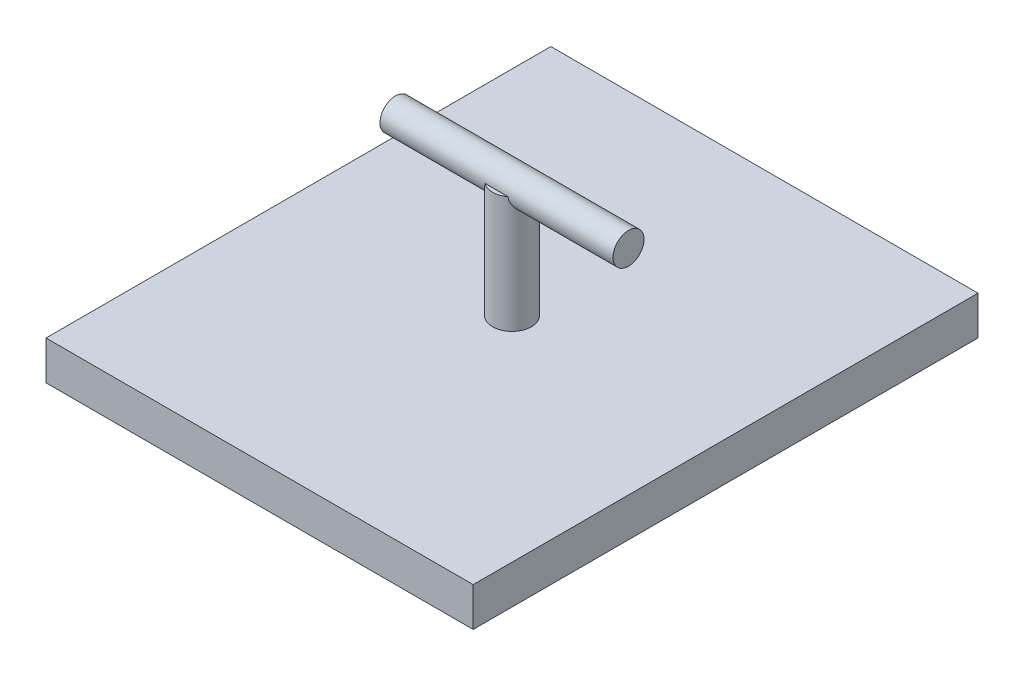
SolidWorks part; units mm, degrees
material "ABS"
ref_plane "前视基准面" through (0, 0, 0) normal (0, 0, 1) x (1, 0, 0)
ref_plane "上视基准面" through (0, 0, 0) normal (0, 1, 0) x (1, 0, 0)
ref_plane "右视基准面" through (0, 0, 0) normal (1, 0, 0) x (0, 0, -1)
sketch "草图1" plane through (0, 0, 0) normal (0, 1, 0) x (1, 0, 0)
  line L0 (-30, 0) -> (30, 0)
  line L1 (-30, 4) -> (30, 4)
  line L2 (-30, 4) -> (-30, -4)
  line L3 (-30, -4) -> (30, -4)
  line L4 (30, 4) -> (30, -4)
  line L5 (-30, 4) -> (30, -4) construction
  line L6 (-30, -4) -> (30, 4) construction
  point P0 (0, 0)
revolve "旋转3" add sketch "草图1" angle 360 about L0
sketch "草图3" plane through (0, 0, 0) normal (0, 1, 0) x (1, 0, 0)
  circle A0 centre (0, 0) radius 5
extrude "凸台-拉伸2" add sketch "草图3" against normal blind 30
sketch "草图5" plane through (0, -30, 0) normal (0, -1, 0) x (1, 0, 0)
  line L1 (-55, 65) -> (55, 65)
  line L2 (-55, 65) -> (-55, -65)
  line L3 (-55, -65) -> (55, -65)
  line L4 (55, 65) -> (55, -65)
  line L5 (-55, 65) -> (55, -65) construction
  line L6 (-55, -65) -> (55, 65) construction
  point P0 (0, 0)
extrude "凸台-拉伸3" add sketch "草图5" along normal blind 10
